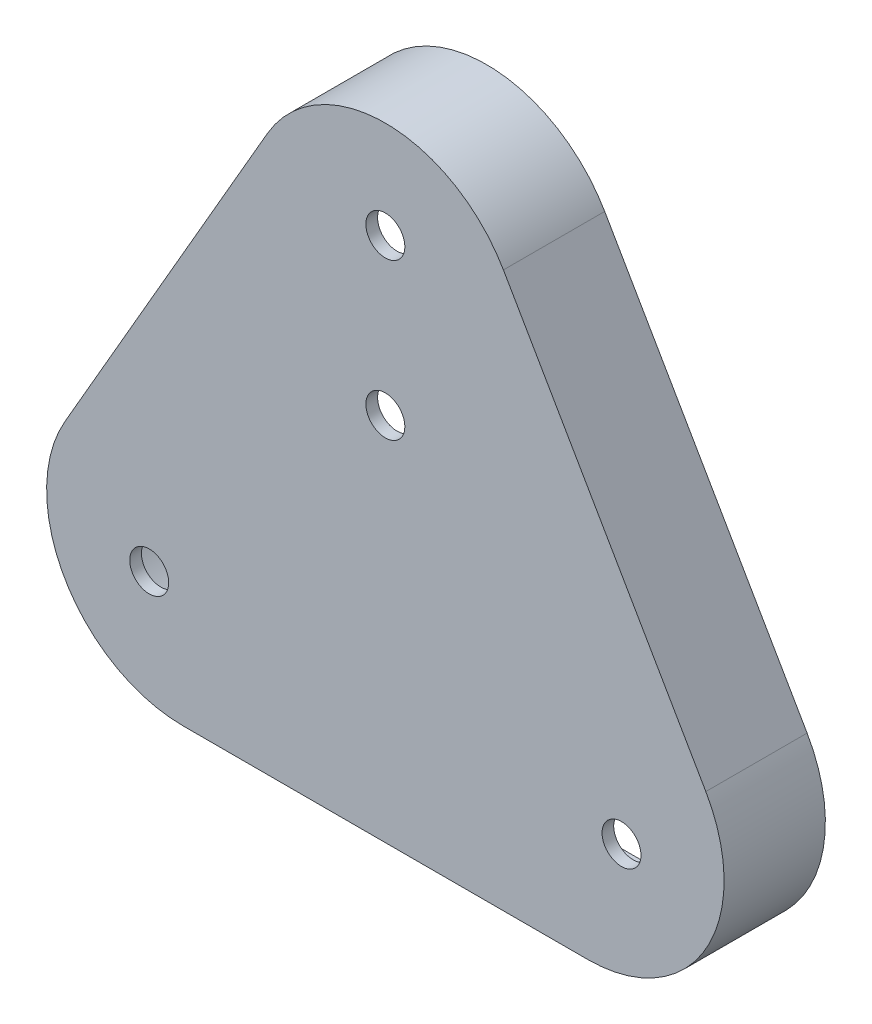
SolidWorks part; units mm, degrees
ref_plane "Plano frontal" through (0, 0, 0) normal (0, 0, 1) x (1, 0, 0)
ref_plane "Plano superior" through (0, 0, 0) normal (0, 1, 0) x (1, 0, 0)
ref_plane "Plano direito" through (0, 0, 0) normal (1, 0, 0) x (0, 0, -1)
sketch "Esboço1" plane through (0, 0, 0) normal (0, 0, 1) x (1, 0, 0)
  line L3 (51.9615, -65) -> (-51.9615, -65)
  line L4 (30.3109, 77.5) -> (82.2724, -12.5)
  line L5 (-82.2724, -12.5) -> (-30.3109, 77.5)
  line L9 (51.9615, -62) -> (-51.9615, -62)
  line L10 (-79.6743, -14) -> (-27.7128, 76)
  line L11 (27.7128, 76) -> (79.6743, -14)
  arc A3 (-82.2724, -12.5) -> (-51.9615, -65) centre (-51.9615, -30) ccw
  arc A4 (51.9615, -65) -> (82.2724, -12.5) centre (51.9615, -30) ccw
  arc A5 (30.3109, 77.5) -> (-30.3109, 77.5) centre (0, 60) ccw
  arc A9 (-79.6743, -14) -> (-51.9615, -62) centre (-51.9615, -30) ccw
  arc A10 (27.7128, 76) -> (-27.7128, 76) centre (0, 60) ccw
  arc A11 (51.9615, -62) -> (79.6743, -14) centre (51.9615, -30) ccw
  dimension "D1" = 3
extrude "Ressalto-extrusão1" add sketch "Esboço1" along normal blind 3
sketch "Esboço2" plane through (0, 0, 3) normal (0, 0, 1) x (1, 0, 0)
  line L0 (-51.9615, -65) -> (51.9615, -65) construction
  line L1 (82.2724, -12.5) -> (30.3109, 77.5) construction
  line L2 (-30.3109, 77.5) -> (-82.2724, -12.5) construction
  line L3 (-51.9615, -65) -> (51.9615, -65)
  line L4 (82.2724, -12.5) -> (30.3109, 77.5)
  line L5 (-30.3109, 77.5) -> (-82.2724, -12.5)
  line L6 (-51.9615, -61) -> (51.9615, -61)
  line L7 (78.8083, -14.5) -> (26.8468, 75.5)
  line L8 (-26.8468, 75.5) -> (-78.8083, -14.5)
  arc A0 (-82.2724, -12.5) -> (-51.9615, -65) centre (-51.9615, -30) ccw construction
  arc A1 (51.9615, -65) -> (82.2724, -12.5) centre (51.9615, -30) ccw construction
  arc A2 (30.3109, 77.5) -> (-30.3109, 77.5) centre (0, 60) ccw construction
  arc A3 (-82.2724, -12.5) -> (-51.9615, -65) centre (-51.9615, -30) ccw
  arc A4 (51.9615, -65) -> (82.2724, -12.5) centre (51.9615, -30) ccw
  arc A5 (30.3109, 77.5) -> (-30.3109, 77.5) centre (0, 60) ccw
  arc A6 (51.9615, -61) -> (78.8083, -14.5) centre (51.9615, -30) ccw
  arc A7 (26.8468, 75.5) -> (-26.8468, 75.5) centre (0, 60) ccw
  arc A8 (-78.8083, -14.5) -> (-51.9615, -61) centre (-51.9615, -30) ccw
  dimension "D1" = 4
extrude "Ressalto-extrusão2" add sketch "Esboço2" along normal blind 20
sketch "Esboço3" plane through (0, 0, 23) normal (0, 0, 1) x (1, 0, 0)
  line L0 (-30.3109, 77.5) -> (-82.2724, -12.5) construction
  line L1 (-51.9615, -65) -> (51.9615, -65) construction
  line L2 (82.2724, -12.5) -> (30.3109, 77.5) construction
  line L3 (-30.3109, 77.5) -> (-82.2724, -12.5)
  line L4 (-51.9615, -65) -> (51.9615, -65)
  line L5 (82.2724, -12.5) -> (30.3109, 77.5)
  arc A0 (-82.2724, -12.5) -> (-51.9615, -65) centre (-51.9615, -30) ccw construction
  arc A1 (51.9615, -65) -> (82.2724, -12.5) centre (51.9615, -30) ccw construction
  arc A2 (30.3109, 77.5) -> (-30.3109, 77.5) centre (0, 60) ccw construction
  arc A3 (-82.2724, -12.5) -> (-51.9615, -65) centre (-51.9615, -30) ccw
  arc A4 (51.9615, -65) -> (82.2724, -12.5) centre (51.9615, -30) ccw
  arc A5 (30.3109, 77.5) -> (-30.3109, 77.5) centre (0, 60) ccw
extrude "Ressalto-extrusão3" add sketch "Esboço3" along normal blind 3
sketch "Esboço4" plane through (0, 0, 26) normal (0, 0, 1) x (1, 0, 0)
  line L0 (0, 0) -> (0, 70) construction
  circle A3 centre (0, 70) radius 5
  circle A4 centre (60.6218, -35) radius 5
  circle A5 centre (-60.6218, -35) radius 5
  circle A6 centre (0, 30) radius 5
  point P13 (0, 0)
  dimension "D1" = 70
  dimension "D2" = 10
  dimension "D4" = 10
  dimension "D5" = 30
  dimension "D3" = 3
extrude "Corte-extrusão1" cut sketch "Esboço4" against normal up to surface (3 mm away) up to face at (0, 0, 23)
